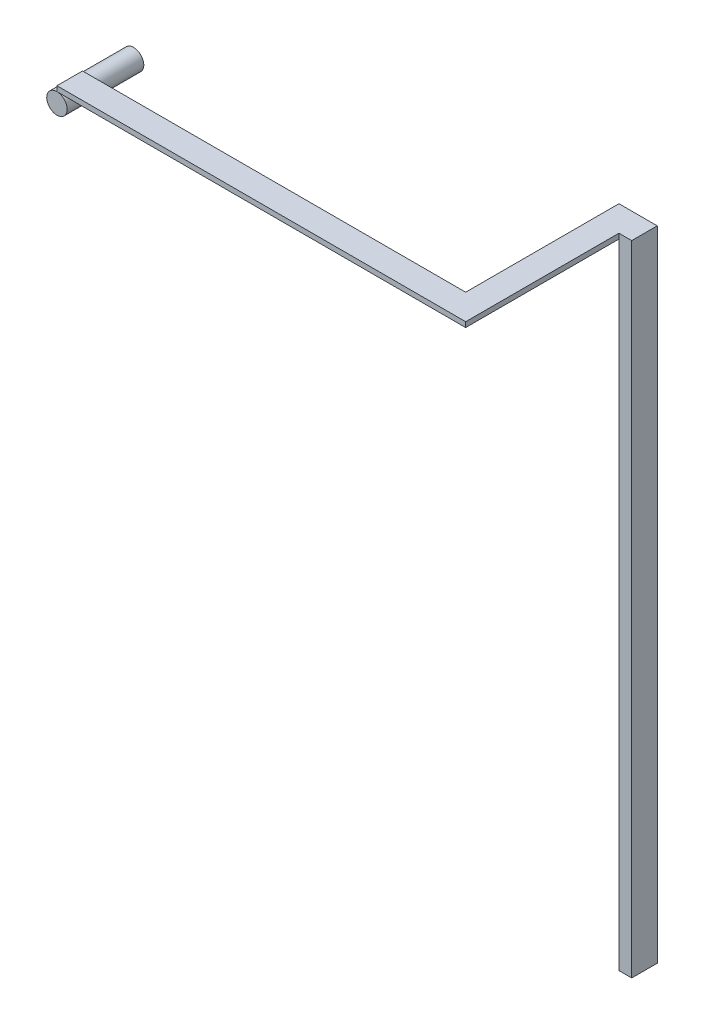
SolidWorks part; units mm, degrees
ref_plane "Front Plane" through (0, 0, 0) normal (0, 0, 1) x (1, 0, 0)
ref_plane "Top Plane" through (0, 0, 0) normal (0, 1, 0) x (1, 0, 0)
ref_plane "Right Plane" through (0, 0, 0) normal (1, 0, 0) x (0, 0, -1)
sketch "Sketch1" plane through (0, 0, 0) normal (0, 0, 1) x (1, 0, 0)
  circle A0 centre (0, 0) radius 4
  dimension "D1" = 8
extrude "Boss-Extrude1" add sketch "Sketch1" along normal blind 30
sketch "Sketch2" plane through (0, 0, 30) normal (0, 0, 1) x (1, 0, 0)
  line L1 (0, 4) -> (160, 4)
  line L2 (0, 4) -> (0, 6)
  line L3 (0, 6) -> (160, 6)
  line L4 (160, 4) -> (160, 6)
  circle A0 centre (0, 0) radius 4 construction
  dimension "D1" = 2
  dimension "D2" = 160
extrude "Boss-Extrude2" add sketch "Sketch2" against normal blind 10 separate body
sketch "Sketch3" plane through (0, 0, 20) normal (0, 0, -1) x (-1, 0, 0)
  line L0 (-160, 6) -> (0, 6) construction
  line L1 (-150, 6) -> (-160, 6)
  line L2 (-150, 6) -> (-150, 4)
  line L3 (-150, 4) -> (-160, 4)
  line L4 (-160, 6) -> (-160, 4)
  line L5 (0, 4) -> (-160, 4) construction
  line L6 (-160, 4) -> (-160, 6) construction
  dimension "D1" = 10
extrude "Boss-Extrude3" add sketch "Sketch3" along normal blind 60
sketch "Sketch5" plane through (160, 0, 0) normal (1, 0, 0) x (0, 0, -1)
  line L1 (40, 6) -> (30, 6)
  line L2 (40, 6) -> (40, -244)
  line L3 (40, -244) -> (30, -244)
  line L4 (30, 6) -> (30, -244)
  dimension "D1" = 10
  dimension "D2" = 250
extrude "Boss-Extrude5" add sketch "Sketch5" along normal blind 5
